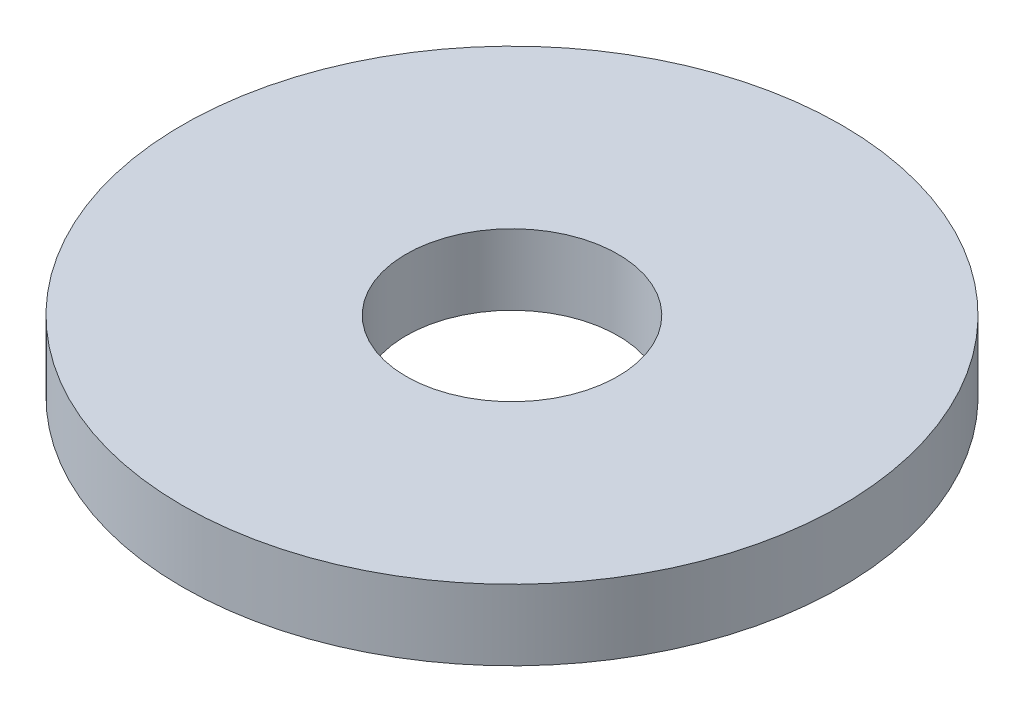
SolidWorks part; units mm, degrees
material "AISI 1035 Stahl"
ref_plane "Plane1" through (0, 0, 0) normal (0, 0, 1) x (1, 0, 0)
ref_plane "Plane2" through (0, 0, 0) normal (0, 1, 0) x (1, 0, 0)
ref_plane "Plane3" through (0, 0, 0) normal (1, 0, 0) x (0, 0, -1)
sketch "Sketch1" plane through (0, 0, 0) normal (0, 1, 0) x (1, 0, 0)
  circle A0 centre (0, 0) radius 14
  dimension "OutsideDia" = 28
extrude "Base-Extrude" add sketch "Sketch1" against normal blind 3
sketch "Sketch2" plane through (0, 0, 0) normal (0, 1, 0) x (-1, 0, 0)
  circle A0 centre (0, 0) radius 4.5
  dimension "HoleDia" = 9
extrude "Type-R" cut sketch "Sketch2" against normal through all
sketch "Sketch3" plane through (0, 0, 0) normal (0, 1, 0) x (-1, 0, 0)
  line L1 (4.5, 4.5) -> (-4.5, 4.5)
  line L2 (4.5, 4.5) -> (4.5, -4.5)
  line L3 (4.5, -4.5) -> (-4.5, -4.5)
  line L4 (-4.5, 4.5) -> (-4.5, -4.5)
  dimension "SquareSize" = 9
  dimension "D1" = 9
  dimension "D2" = 4.5
  dimension "D3" = 4.5
extrude "Type-V" [suppressed] cut sketch "Sketch3" against normal through all
equation "\"D1@Sketch3\" = \"SquareSize@Sketch3\""
equation "\"D2@Sketch3\" = \"SquareSize@Sketch3\" / 2"
equation "\"D3@Sketch3\" = \"D1@Sketch3\" / 2"
